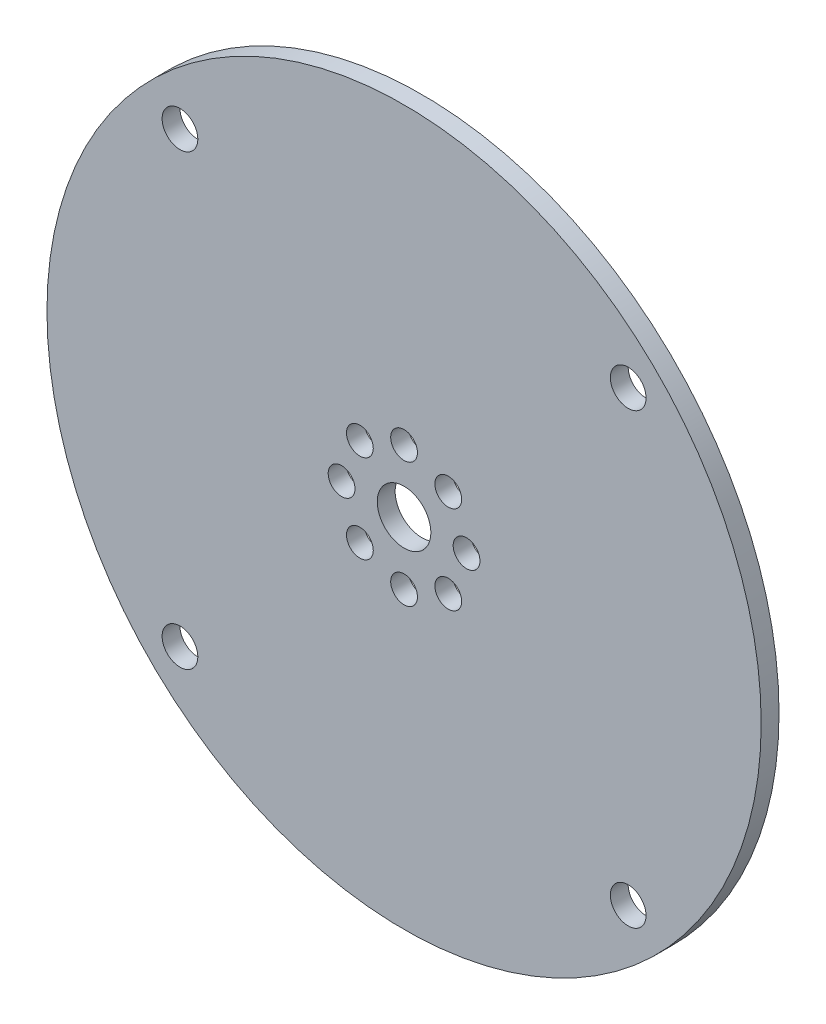
SolidWorks part; units mm, degrees
ref_plane "前视基准面" through (0, 0, 0) normal (0, 0, 1) x (1, 0, 0)
ref_plane "上视基准面" through (0, 0, 0) normal (0, 1, 0) x (1, 0, 0)
ref_plane "右视基准面" through (0, 0, 0) normal (1, 0, 0) x (0, 0, -1)
sketch "Model" plane through (0, 0, 0) normal (0, 0, 1) x (1, 0, 0)
  circle A0 centre (2653.6497, 1953.4895) radius 1.5
  circle A1 centre (2653.6497, 1939.4895) radius 1.5
  circle A2 centre (2628.5474, 1971.5918) radius 2
  circle A3 centre (2678.752, 1971.5918) radius 2
  circle A4 centre (2653.6497, 1946.4895) radius 40
  circle A5 centre (2628.5474, 1921.3872) radius 2
  circle A6 centre (2678.752, 1921.3872) radius 2
  circle A7 centre (2646.6497, 1946.4895) radius 1.5
  circle A8 centre (2660.6497, 1946.4895) radius 1.5
  circle A9 centre (2653.6497, 1946.4895) radius 3
  circle A10 centre (2648.7, 1941.5398) radius 1.5
  circle A11 centre (2658.5995, 1941.5398) radius 1.5
  circle A12 centre (2648.7, 1951.4393) radius 1.5
  circle A13 centre (2658.5995, 1951.4393) radius 1.5
  spline S0 degree 3 poles (0, 0) (0.3333, 0) (0.6667, 0) (1, 0) knots 0 0 0 0 1 1 1 1
extrude "凸台-拉伸1" add sketch "Model" along normal blind 2 contours A4 A13 A12 A11 A10 A9 A8 A7 A6 A5 A0 A1 A2 A3
